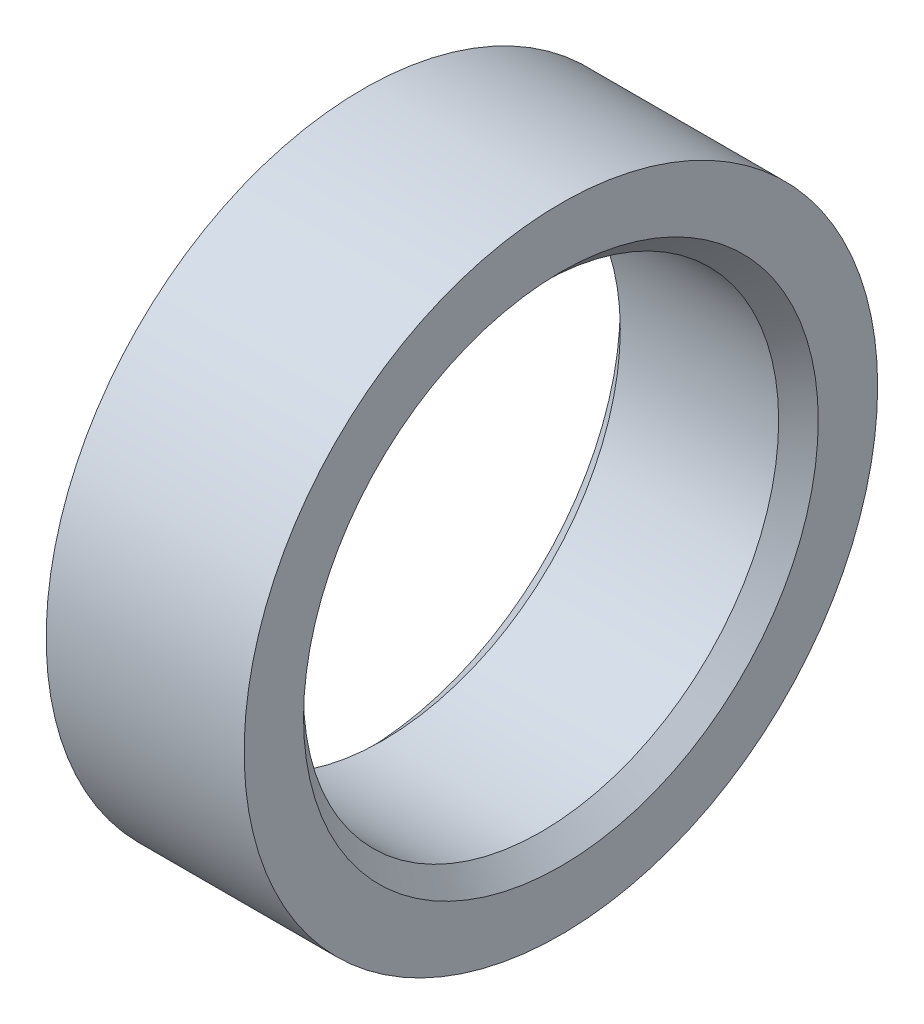
SolidWorks part; units mm, degrees
ref_plane "Płaszczyzna przednia" through (0, 0, 0) normal (0, 0, 1) x (1, 0, 0)
ref_plane "Płaszczyzna górna" through (0, 0, 0) normal (0, 1, 0) x (1, 0, 0)
ref_plane "Płaszczyzna prawa" through (0, 0, 0) normal (1, 0, 0) x (0, 0, -1)
sketch "Szkic1" plane through (0, 0, 0) normal (1, 0, 0) x (0, 0, -1)
  circle A0 centre (0, 0) radius 8
  circle A1 centre (0, 0) radius 6
  dimension "D1" = 12
  dimension "D2" = 16
extrude "Dodanie-wyciągnięcie1" add sketch "Szkic1" along normal blind 5
chamfer "Sfazowanie1" distance 0.5 angle 45 2 edges at (0, 0, -6) (5, 0, -6)
